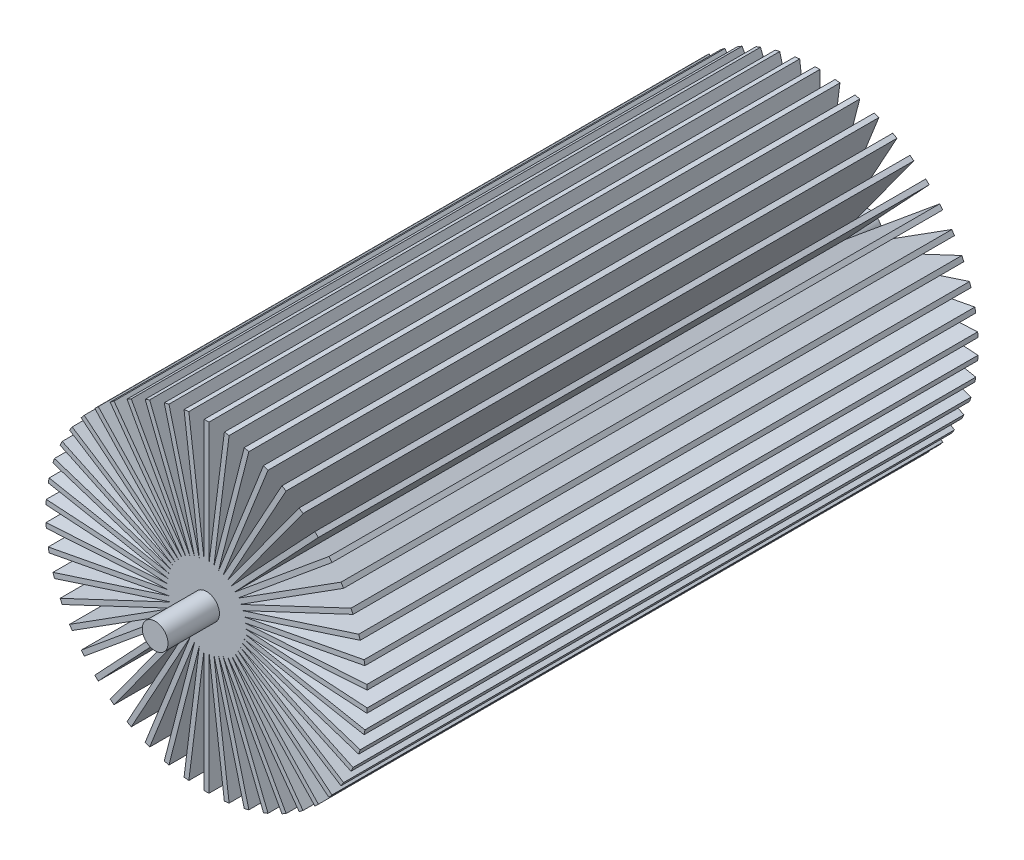
SolidWorks part; units mm, degrees
ref_plane "Front Plane" through (0, 0, 0) normal (0, 0, 1) x (1, 0, 0)
ref_plane "Top Plane" through (0, 0, 0) normal (0, 1, 0) x (1, 0, 0)
ref_plane "Right Plane" through (0, 0, 0) normal (1, 0, 0) x (0, 0, -1)
sketch "Sketch4" plane through (0, 0, 0) normal (0, 0, 1) x (1, 0, 0)
  circle A0 centre (0, 0) radius 4
  dimension "D1" = 8
extrude "Boss-Extrude1" add sketch "Sketch4" along normal mid plane 222
sketch "Sketch6" plane through (0, 0, 0) normal (0, 0, 1) x (1, 0, 0)
  line L0 (-0.75, 0) -> (0.75, 0)
  line L1 (-0.75, 0) -> (-0.75, 50)
  line L2 (0.75, 0) -> (0.75, 50)
  line L3 (-0.75, 50) -> (0.75, 50)
  point P0 (0, 0)
  dimension "D1" = 1.5
  dimension "D2" = 50
extrude "Boss-Extrude2" add sketch "Sketch6" along normal mid plane 190
pattern_circular "CirPattern1" count 50 over 360 about axis through (0, 0, 0) along (0, 0, 1) of "Boss-Extrude2"
